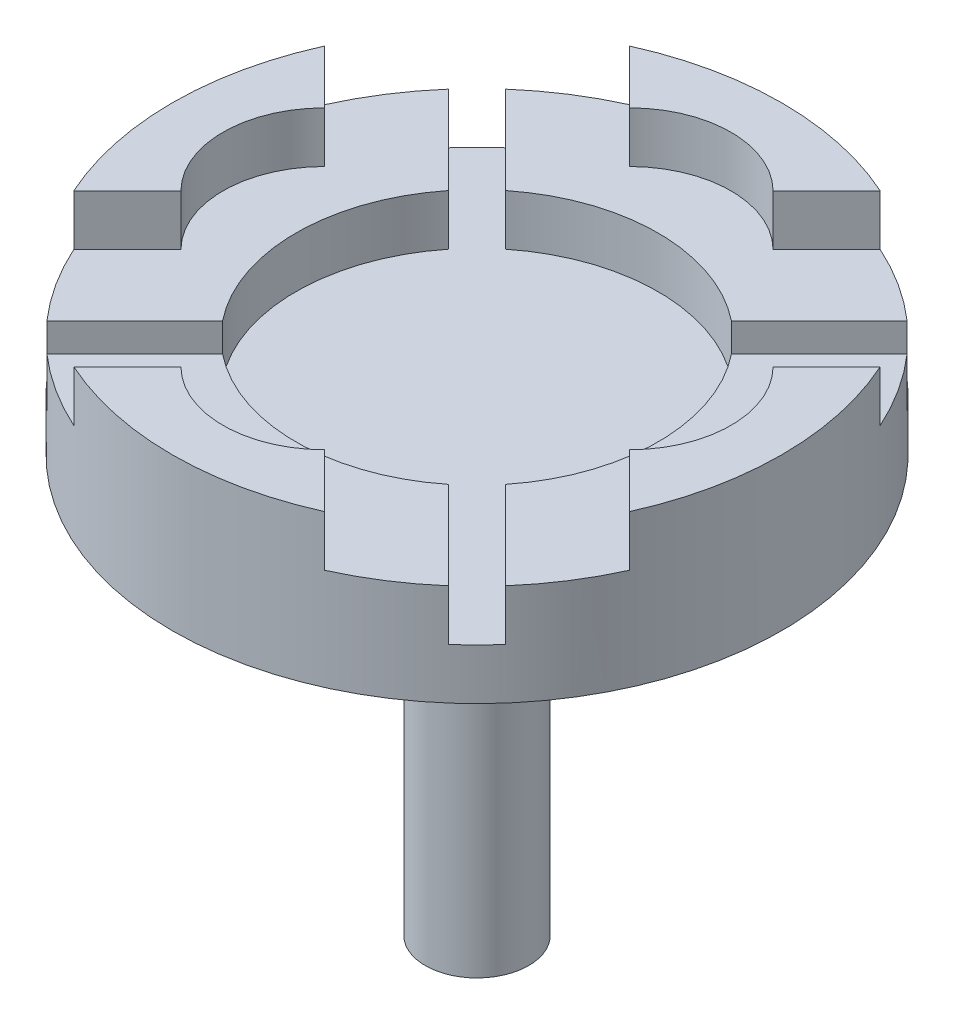
SolidWorks part; units mm, degrees
ref_plane "前视基准面" through (0, 0, 0) normal (0, 0, 1) x (1, 0, 0)
ref_plane "上视基准面" through (0, 0, 0) normal (0, 1, 0) x (1, 0, 0)
ref_plane "右视基准面" through (0, 0, 0) normal (1, 0, 0) x (0, 0, -1)
other "Configuration Table"
sketch "草图1" plane through (0, 0, 0) normal (0, 1, 0) x (1, 0, 0)
  line L0 (0, 0) -> (106.066, -106.066)
  line L1 (0, 0) -> (-106.066, 106.066)
  line L2 (106.066, 106.066) -> (-106.066, -106.066)
  circle A0 centre (0, 0) radius 150
  circle A1 centre (0, 0) radius 75
  circle A2 centre (0, 0) radius 89.1
extrude "凸台-拉伸1" add sketch "草图1" along normal blind 50 contours A0
sketch "草图2" plane through (0, 50, 0) normal (0, 1, 0) x (1, 0, 0)
  line L0 (0, 0) -> (106.066, -106.066)
  line L1 (0, 0) -> (-106.066, 106.066)
  line L2 (106.066, 106.066) -> (-106.066, -106.066)
  line L3 (0, 0) -> (-7.0711, 7.0711)
  line L4 (98.9949, 113.1371) -> (-113.1371, -98.9949)
  line L5 (113.1371, 98.9949) -> (-98.9949, -113.1371)
  line L6 (0, 0) -> (150, 0)
  line L7 (98.9949, -113.1371) -> (-113.1371, 98.9949)
  line L8 (113.1371, -98.9949) -> (-98.9949, 113.1371)
  circle A0 centre (0, 0) radius 89.1
  circle A1 centre (0, 0) radius 150 construction
  point P15 (7.0711, -7.0711)
  circle M7 centre (0, 0) radius 150
extrude "切除-拉伸1" cut sketch "草图2" against normal blind 25 contours A0 L7 L0 M7 | A0 L0 L8 M7 | L0 A0 L8 L5 | L7 A0 L0 L5 | L5 A0 L7 | L2 A0 L5 L7 | L4 A0 L2 L7 | A0 L2 L5 M7 | A0 L4 L2 M7 | L7 A0 L4 | L1 A0 L7 L4 | L8 A0 L1 L4 | L7 L5 L0 L2 | L7 L2 L1 L4 | L6 L8 L2 | L6 L0 L5 | L2 L8 L4 L1 | L2 A0 L4 L8 | A0 L5 L2 M7 | L5 A0 L2 L8 | A0 L2 L4 M7 | A0 L1 L7 M7 | A0 L8 L1 M7 | L6 A0 L5 | L8 A0 L6 | L4 A0 L8
sketch "草图3" plane through (0, 50, 0) normal (0, 1, 0) x (1, 0, 0)
  line L0 (0, 0) -> (0, -75)
  line L1 (0, -75) -> (61.7157, -136.7157)
  line L2 (0, -75) -> (-61.7157, -136.7157)
  line L3 (0, 0) -> (75, 0)
  line L4 (0, 0) -> (75, -75)
  line L5 (0, 75) -> (61.7157, 136.7157)
  line L6 (0, 75) -> (-61.7157, 136.7157)
  line L7 (75, 0) -> (136.7157, 61.7157)
  line L8 (75, 0) -> (136.7157, -61.7157)
  line L9 (-75, 0) -> (-136.7157, 61.7157)
  line L10 (-75, 0) -> (-136.7157, -61.7157)
  circle A0 centre (0, 0) radius 75
  circle A1 centre (0, -75) radius 50
  arc A2 (-98.759, -112.9011) -> (98.759, -112.9011) centre (0, 0) ccw construction
  circle A3 centre (0, 75) radius 50
  circle A4 centre (75, 0) radius 50
  circle A5 centre (-75, 0) radius 50
  circle A6 centre (0, 0) radius 150
  arc M15 (-112.9011, 98.759) -> (-112.9011, -98.759) centre (0, 0) ccw
extrude "凸台-拉伸2" add sketch "草图3" along normal blind 25 contours A5 L9 L10 M15 | L5 A6 L6 A3 | L8 A6 L7 A4 | L2 A6 L1 A1
sketch "草图4" plane through (0, 0, 0) normal (0, -1, 0) x (1, 0, 0)
  line L0 (0, 0) -> (0, 3)
  circle A1 centre (0, 0) radius 50
  circle A2 centre (0, 0) radius 10
extrude "凸台-拉伸3" add sketch "草图4" along normal blind 30
sketch "草图5" plane through (0, -30, 0) normal (0, -1, 0) x (1, 0, 0)
  circle A0 centre (0, 0) radius 25.46
extrude "凸台-拉伸4" add sketch "草图5" along normal blind 175
sketch "草图6" plane through (0, -205, 0) normal (0, -1, 0) x (1, 0, 0)
  circle A0 centre (0, 0) radius 10
extrude "凸台-拉伸5" add sketch "草图6" along normal blind 10
